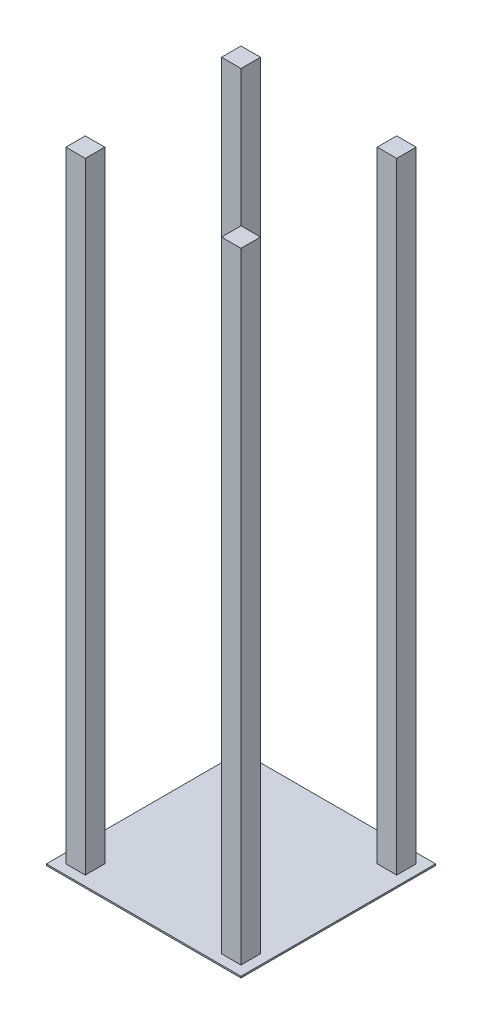
SolidWorks part; units mm, degrees
ref_plane "Front Plane" through (0, 0, 0) normal (0, 0, 1) x (1, 0, 0)
ref_plane "Top Plane" through (0, 0, 0) normal (0, 1, 0) x (1, 0, 0)
ref_plane "Right Plane" through (0, 0, 0) normal (1, 0, 0) x (0, 0, -1)
sketch "Sketch1" plane through (0, 0, 0) normal (0, 1, 0) x (1, 0, 0)
  line L1 (-127, 127) -> (127, 127)
  line L2 (-127, 127) -> (-127, -127)
  line L3 (-127, -127) -> (127, -127)
  line L4 (127, 127) -> (127, -127)
  line L5 (-127, 127) -> (127, -127) construction
  line L6 (-127, -127) -> (127, 127) construction
  point P0 (0, 0)
  dimension "D1" = 254
extrude "Boss-Extrude1" add sketch "Sketch1" along normal blind 2
sketch "Sketch2" plane through (0, 2, 0) normal (0, 1, 0) x (1, 0, 0)
  line L0 (127, 127) -> (-127, 127) construction
  line L1 (-114.3, 114.3) -> (-88.9, 114.3)
  line L2 (-114.3, 114.3) -> (-114.3, 88.9)
  line L3 (-114.3, 88.9) -> (-88.9, 88.9)
  line L4 (-88.9, 114.3) -> (-88.9, 88.9)
  line L5 (-114.3, 114.3) -> (-88.9, 88.9) construction
  line L6 (-114.3, 88.9) -> (-88.9, 114.3) construction
  line L7 (-127, 127) -> (-127, -127) construction
  line L8 (-114.3, -88.9) -> (-88.9, -88.9)
  line L9 (-114.3, -88.9) -> (-114.3, -114.3)
  line L10 (-114.3, -114.3) -> (-88.9, -114.3)
  line L11 (-88.9, -88.9) -> (-88.9, -114.3)
  line L12 (-114.3, -88.9) -> (-88.9, -114.3) construction
  line L13 (-114.3, -114.3) -> (-88.9, -88.9) construction
  line L14 (88.9, -88.9) -> (114.3, -88.9)
  line L15 (88.9, -88.9) -> (88.9, -114.3)
  line L16 (88.9, -114.3) -> (114.3, -114.3)
  line L17 (114.3, -88.9) -> (114.3, -114.3)
  line L18 (88.9, -88.9) -> (114.3, -114.3) construction
  line L19 (88.9, -114.3) -> (114.3, -88.9) construction
  line L20 (88.9, 114.3) -> (114.3, 114.3)
  line L21 (88.9, 114.3) -> (88.9, 88.9)
  line L22 (88.9, 88.9) -> (114.3, 88.9)
  line L23 (114.3, 114.3) -> (114.3, 88.9)
  line L24 (88.9, 114.3) -> (114.3, 88.9) construction
  line L25 (88.9, 88.9) -> (114.3, 114.3) construction
  line L26 (127, -127) -> (127, 127) construction
  line L27 (-127, -127) -> (127, -127) construction
  point P0 (-101.6, 101.6)
  point P5 (-70.7251, 69.5263)
  point P10 (-101.6, -101.6)
  point P15 (101.6, -101.6)
  point P20 (101.6, 101.6)
  point P25 (70.7251, -72.3234)
  point P26 (72.723, 76.2)
  dimension "D1" = 25.4
  dimension "D2" = 25.4
  dimension "D3" = 25.4
  dimension "D4" = 25.4
  dimension "D5" = 25.4
  dimension "D6" = 25.4
  dimension "D7" = 25.4
  dimension "D8" = 25.4
  dimension "D9" = 25.4
  dimension "D10" = 25.4
  dimension "D11" = 25.4
  dimension "D12" = 25.4
extrude "Boss-Extrude2" add sketch "Sketch2" along normal blind 810
